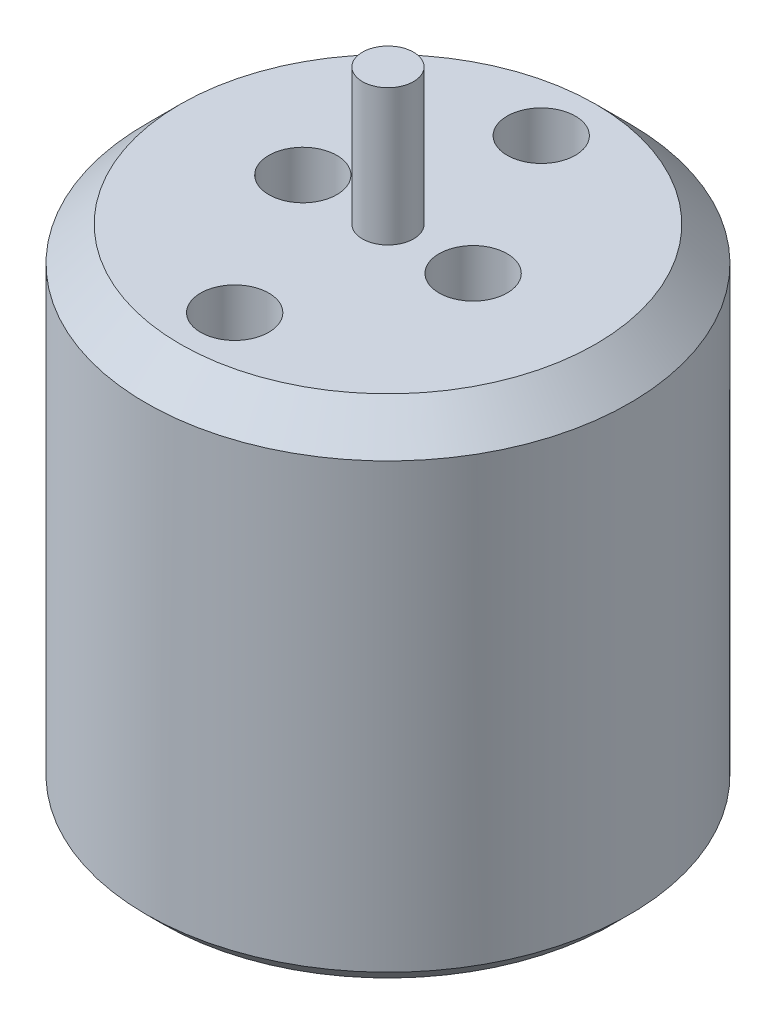
SolidWorks part; units mm, degrees
ref_plane "Front Plane" through (0, 0, 0) normal (0, 0, 1) x (1, 0, 0)
ref_plane "Top Plane" through (0, 0, 0) normal (0, 1, 0) x (1, 0, 0)
ref_plane "Right Plane" through (0, 0, 0) normal (1, 0, 0) x (0, 0, -1)
sketch "Sketch1" plane through (0, 0, 0) normal (0, 1, 0) x (1, 0, 0)
  circle A0 centre (0, 0) radius 7.1
  dimension "D1" = 14.2
extrude "Boss-Extrude1" add sketch "Sketch1" along normal blind 14.5
sketch "Sketch2" plane through (0, 14.5, 0) normal (0, 1, 0) x (1, 0, 0)
  circle A0 centre (0, 0) radius 0.75
  dimension "D1" = 1.5
extrude "Boss-Extrude2" add sketch "Sketch2" along normal blind 4
sketch "Sketch3" plane through (0, 0, 0) normal (0, -1, 0) x (1, 0, 0)
  line L0 (4.5, 0) -> (-4.5, 0) construction
  line L1 (0, -4.5) -> (0, 4.5) construction
  circle A0 centre (-4.5, 0) radius 1
  circle A1 centre (0, 4.5) radius 1
  circle A2 centre (0, -4.5) radius 1
  circle A3 centre (4.5, 0) radius 1
  circle A4 centre (0, 0) radius 4.5 construction
  point P3 (0, 0)
  point P8 (0, 0)
  dimension "D1" = 2
  dimension "D2" = 9
extrude "Cut-Extrude1" cut sketch "Sketch3" against normal blind 4
sketch "Sketch4" plane through (0, 14.5, 0) normal (0, 1, 0) x (1, 0, 0)
  line L0 (2.5, 0) -> (-2.5, 0) construction
  line L1 (0, 4.5) -> (0, -4.5) construction
  circle A0 centre (-2.5, 0) radius 1
  circle A1 centre (0, 4.5) radius 1
  circle A2 centre (0, -4.5) radius 1
  circle A3 centre (2.5, 0) radius 1
  point P15 (0, 0)
  point P20 (0, 0)
  dimension "D1" = 2
  dimension "D2" = 9
  dimension "D3" = 5
extrude "Cut-Extrude2" cut sketch "Sketch4" against normal blind 4
chamfer "Chamfer1" distance 1 angle 45 1 edges at (0, 14.5, 7.1)
chamfer "Chamfer2" distance 0.5 angle 45 1 edges at (0, 0, 7.1)
ref_point "Point1"
ref_point "Point2"
ref_plane "Plane1" through (0, 0, 0) normal (0, 0, 1) x (1, 0, 0)
ref_point "Point3"
ref_plane "Plane2" through (0, 0, 0) normal (-0.7071, 0, 0.7071) x (0, -1, 0)
